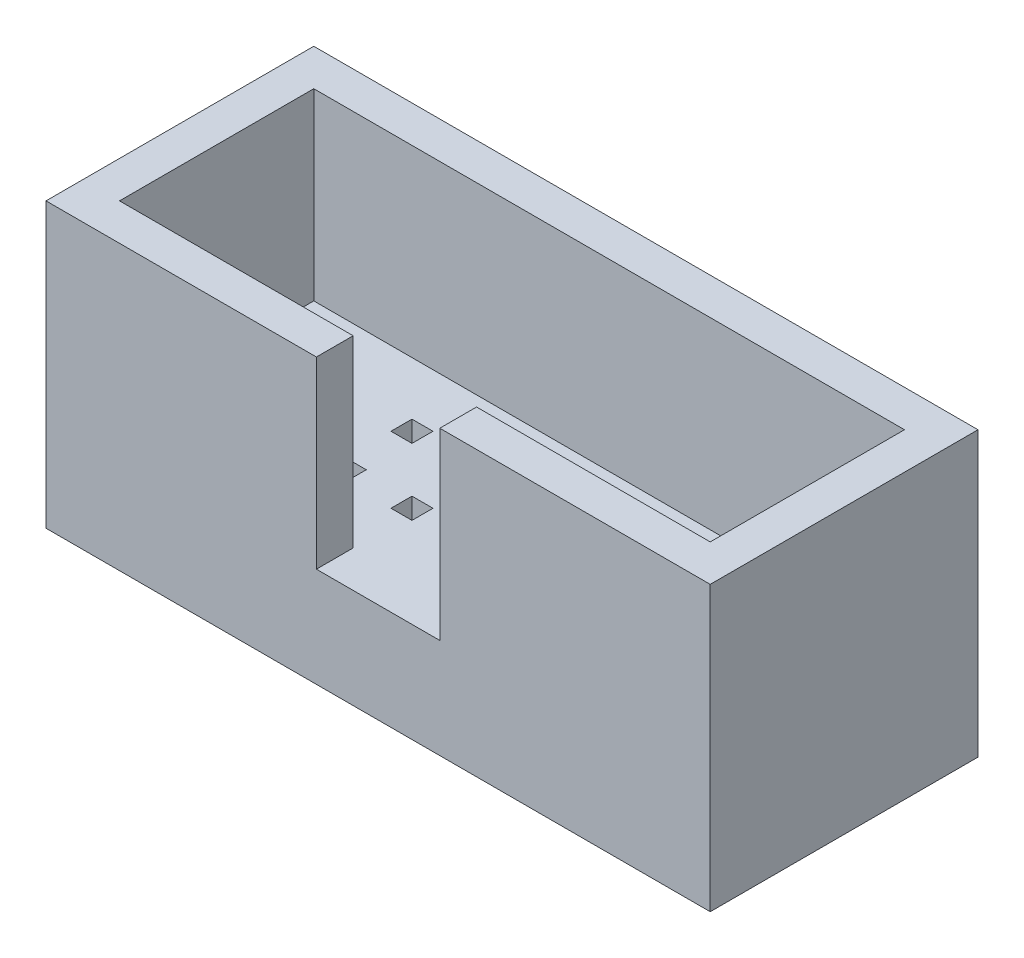
SolidWorks part; units mm, degrees
ref_plane "Front Plane" through (0, 0, 0) normal (0, 0, 1) x (1, 0, 0)
ref_plane "Top Plane" through (0, 0, 0) normal (0, 1, 0) x (1, 0, 0)
ref_plane "Right Plane" through (0, 0, 0) normal (1, 0, 0) x (0, 0, -1)
sketch "Sketch1" plane through (0, 0, 0) normal (0, 1, 0) x (1, 0, 0)
  line L1 (-6.325, -2.55) -> (6.325, -2.55)
  line L2 (-6.325, -2.55) -> (-6.325, 2.55)
  line L3 (-6.325, 2.55) -> (6.325, 2.55)
  line L4 (6.325, -2.55) -> (6.325, 2.55)
  line L5 (-6.325, -2.55) -> (6.325, 2.55) construction
  line L6 (-6.325, 2.55) -> (6.325, -2.55) construction
  point P0 (0, 0)
  dimension "D1" = 12.65
  dimension "D2" = 5.1
extrude "Boss-Extrude1" add sketch "Sketch1" along normal blind 5.4
sketch "Sketch2" plane through (0, 5.4, 0) normal (0, 1, 0) x (1, 0, 0)
  line L1 (-5.625, -1.85) -> (5.625, -1.85)
  line L2 (-5.625, -1.85) -> (-5.625, 1.85)
  line L3 (-5.625, 1.85) -> (5.625, 1.85)
  line L4 (5.625, -1.85) -> (5.625, 1.85)
  line L5 (-5.625, -1.85) -> (5.625, 1.85) construction
  line L6 (-5.625, 1.85) -> (5.625, -1.85) construction
  point P0 (0, 0)
  dimension "D1" = 11.25
  dimension "D2" = 3.7
extrude "Cut-Extrude1" cut sketch "Sketch2" against normal blind 3.5
sketch "Sketch3" plane through (0, 0, 2.55) normal (0, 0, 1) x (1, 0, 0)
  line L0 (0, 0) -> (0, 5.8864) construction
  line L1 (-1.175, 5.4) -> (1.175, 5.4)
  line L2 (-1.175, 5.4) -> (-1.175, 1.9)
  line L3 (1.175, 5.4) -> (1.175, 1.9)
  line L4 (-1.175, 1.9) -> (1.175, 1.9)
  line L5 (-6.325, 5.4) -> (6.325, 5.4) construction
  dimension "D1" = 2.35
  dimension "D2" = 3.5
  dimension "D3" = 1.175
extrude "Cut-Extrude2" cut sketch "Sketch3" against normal up to next
sketch "Sketch4" plane through (0, 0, 0) normal (0, -1, 0) x (1, 0, 0)
  line L0 (0, 0) -> (-2.54, 0) construction
  line L1 (-2.54, 0) -> (-2.54, 0.635) construction
  line L3 (-2.74, 0.435) -> (-2.34, 0.435)
  line L4 (-2.74, 0.435) -> (-2.74, 0.835)
  line L5 (-2.74, 0.835) -> (-2.34, 0.835)
  line L6 (-2.34, 0.435) -> (-2.34, 0.835)
  line L7 (-2.74, 0.435) -> (-2.34, 0.835) construction
  line L8 (-2.74, 0.835) -> (-2.34, 0.435) construction
  dimension "D1" = 2.54
  dimension "D2" = 0.635
  dimension "D3" = 0.4
  dimension "D4" = 0.4
extrude "Cut-Extrude5" cut sketch "Sketch4" against normal up to next
pattern_linear "LPattern1" count 5 spacing 1.27 along (1, 0, 0) count 2 spacing 1.27 along (0, 0, -1) of "Cut-Extrude5"
